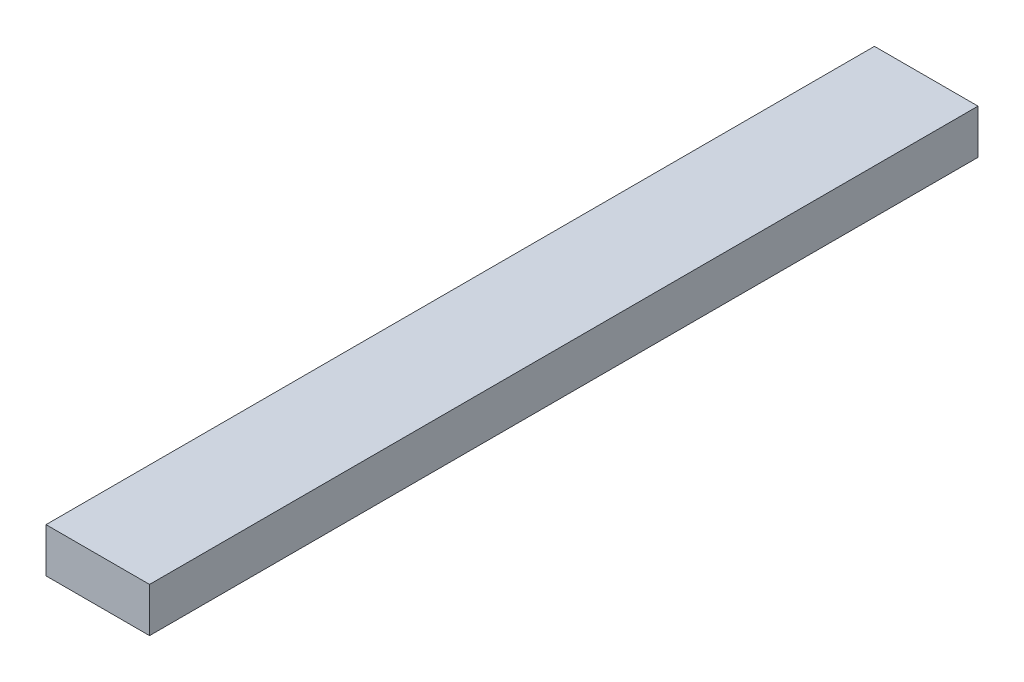
SolidWorks part; units mm, degrees
material "Pine"
ref_plane "Front Plane" through (0, 0, 0) normal (0, 0, 1) x (1, 0, 0)
ref_plane "Top Plane" through (0, 0, 0) normal (0, 1, 0) x (1, 0, 0)
ref_plane "Right Plane" through (0, 0, 0) normal (1, 0, 0) x (0, 0, -1)
sketch "Sketch1" plane through (0, 0, 0) normal (0, 0, 1) x (1, 0, 0)
  line L1 (0, 0) -> (88.9, 0)
  line L2 (0, 0) -> (0, 38.1)
  line L3 (0, 38.1) -> (88.9, 38.1)
  line L4 (88.9, 0) -> (88.9, 38.1)
  dimension "D1" = 88.9
  dimension "D2" = 38.1
extrude "Boss-Extrude1" add sketch "Sketch1" along normal blind 711.2
sketch "Sketch2" plane through (0, 0, 0) normal (0, 0, -1) x (-1, 0, 0)
  line L1 (-88.9, 0) -> (-88.9, 38.1) construction
  line L2 (0, 38.1) -> (0, 0) construction
  line L3 (-44.45, 19.05) -> (-88.9, 19.05) construction
  line L4 (-44.45, 19.05) -> (0, 19.05) construction
  circle A0 centre (-66.675, 19.05) radius 0.8763
  circle A1 centre (-22.225, 19.05) radius 0.8763
  dimension "D1" = 1.7526
sketch "Sketch3" plane through (0, 0, 0) normal (0, -1, 0) x (1, 0, 0)
  line L0 (44.45, 711.2) -> (44.45, 666.75) construction
  line L1 (0, 711.2) -> (88.9, 711.2) construction
  line L2 (44.45, 666.75) -> (44.45, 622.3) construction
  line L3 (88.9, 355.6) -> (0, 355.6) construction
  line L4 (88.9, 711.2) -> (88.9, 0) construction
  line L5 (0, 711.2) -> (0, 0) construction
  line L6 (44.45, 355.6) -> (44.45, 400.05) construction
  line L7 (44.45, 355.6) -> (44.45, 311.15) construction
  circle A0 centre (44.45, 688.975) radius 0.8763
  circle A1 centre (44.45, 644.525) radius 0.8763
  circle A2 centre (44.45, 22.225) radius 0.8763
  circle A3 centre (44.45, 66.675) radius 0.8763
  circle A4 centre (44.45, 333.375) radius 0.8763
  circle A5 centre (44.45, 377.825) radius 0.8763
  dimension "D2" = 1.7526
  dimension "D4" = 1.7526
  dimension "D1" = 88.9
  dimension "D3" = 88.9
equation "\"length\"= 20"
equation "\"length\"= 22"
equation "\"length\"= 36"
equation "\"length\"= 26"
equation "\"length\"= 27"
equation "\"length\"= 28"
equation "\"length\"= 39"
equation "\"length\"= 96"
equation "\"length\"= 30"
equation "\"length\"= 32"
